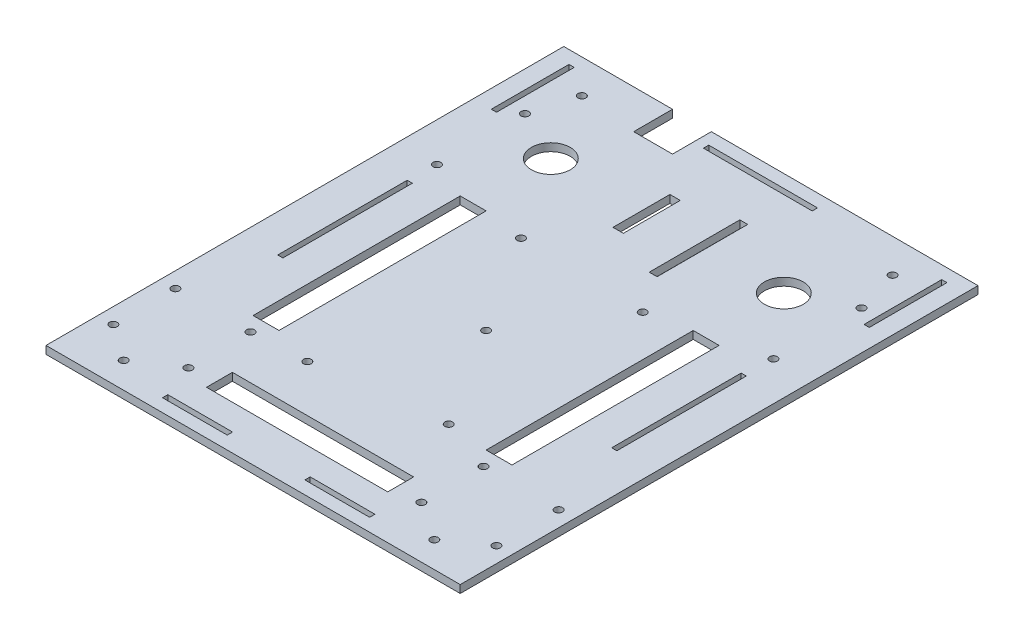
SolidWorks part; units mm, degrees
ref_plane "Front Plane" through (0, 0, 0) normal (0, 0, 1) x (1, 0, 0)
ref_plane "Top Plane" through (0, 0, 0) normal (0, 1, 0) x (1, 0, 0)
ref_plane "Right Plane" through (0, 0, 0) normal (1, 0, 0) x (0, 0, -1)
sketch "Sketch1" plane through (0, 0, 0) normal (0, 1, 0) x (1, 0, 0)
  line L1 (80, -100) -> (-80, -100)
  line L2 (80, -100) -> (80, 100)
  line L3 (80, 100) -> (-80, 100)
  line L4 (-80, -100) -> (-80, 100)
  line L5 (80, -100) -> (-80, 100) construction
  line L6 (80, 100) -> (-80, -100) construction
  point P0 (0, 0)
  dimension "D1" = 200
  dimension "D2" = 160
extrude "Boss-Extrude1" add sketch "Sketch1" along normal blind 3
sketch "Sketch2" plane through (0, 3, 0) normal (0, 1, 0) x (1, 0, 0)
  line L0 (-80, -100) -> (80, -100) construction
  line L1 (-80, 100) -> (-80, -100) construction
  line L2 (-3.268, 0) -> (0, 0) construction
  line L3 (0, 0) -> (0, -105.3922) construction
  line L4 (40, -92.95) -> (40, -95)
  line L5 (-40, -92.95) -> (-15, -92.95)
  line L6 (-40, -92.95) -> (-40, -95)
  line L7 (-40, -95) -> (-15, -95)
  line L8 (-15, -92.95) -> (-15, -95)
  line L9 (-40, -92.95) -> (-15, -95) construction
  line L10 (-40, -95) -> (-15, -92.95) construction
  line L11 (15, -92.95) -> (15, -95)
  line L12 (40, -95) -> (15, -95)
  line L13 (40, -92.95) -> (15, -92.95)
  line L14 (80, 100) -> (-80, 100) construction
  line L15 (65.5, -25) -> (63.5, -25)
  line L16 (-65.5, -25) -> (-63.5, -25)
  line L17 (-65.5, -25) -> (-65.5, 25)
  line L18 (-65.5, 25) -> (-63.5, 25)
  line L19 (-63.5, -25) -> (-63.5, 25)
  line L20 (-65.5, -25) -> (-63.5, 25) construction
  line L21 (-65.5, 25) -> (-63.5, -25) construction
  line L22 (63.5, -25) -> (63.5, 25)
  line L23 (65.5, -25) -> (65.5, 25)
  line L24 (65.5, 25) -> (63.5, 25)
  line L25 (73, 65) -> (70.98, 65)
  line L26 (-23, 85) -> (-38, 85)
  line L27 (-23, 85) -> (-23, 100)
  line L28 (-23, 100) -> (-38, 100)
  line L29 (-38, 85) -> (-38, 100)
  line L30 (-23, 85) -> (-38, 100) construction
  line L31 (-23, 100) -> (-38, 85) construction
  line L32 (23, 92.95) -> (-19, 92.95)
  line L33 (23, 92.95) -> (23, 95)
  line L34 (23, 95) -> (-19, 95)
  line L35 (-19, 92.95) -> (-19, 95)
  line L36 (23, 92.95) -> (-19, 95) construction
  line L37 (23, 95) -> (-19, 92.95) construction
  line L38 (-73, 95) -> (-70.98, 95)
  line L39 (-73, 95) -> (-73, 65)
  line L40 (-73, 65) -> (-70.98, 65)
  line L41 (-70.98, 95) -> (-70.98, 65)
  line L42 (-73, 95) -> (-70.98, 65) construction
  line L43 (-73, 65) -> (-70.98, 95) construction
  line L44 (70.98, 95) -> (70.98, 65)
  line L45 (73, 95) -> (73, 65)
  line L46 (73, 95) -> (70.98, 95)
  line L48 (-10, 49) -> (-6, 49)
  line L49 (-10, 49) -> (-10, 71)
  line L50 (-10, 71) -> (-6, 71)
  line L51 (-6, 49) -> (-6, 71)
  line L52 (-10, 49) -> (-6, 71) construction
  line L53 (-10, 71) -> (-6, 49) construction
  line L54 (15.05, 41) -> (12, 41)
  line L55 (15.05, 41) -> (15.05, 76)
  line L56 (15.05, 76) -> (12, 76)
  line L57 (12, 41) -> (12, 76)
  line L58 (15.05, 41) -> (12, 76) construction
  line L59 (15.05, 76) -> (12, 41) construction
  circle A0 centre (-60, -90) radius 1.5
  circle A1 centre (60, -90) radius 1.5
  circle A2 centre (0, -10) radius 1.5
  circle A3 centre (-65, 70) radius 1.5
  circle A4 centre (65, 70) radius 1.5
  point P14 (-27.5, -93.975)
  point P29 (-64.5, 0)
  point P38 (-30.5, 92.5)
  point P43 (2, 93.975)
  point P48 (-71.99, 80)
  point P57 (-8, 60)
  point P62 (13.525, 58.5)
  dimension "D1" = 3
  dimension "D4" = 3
  dimension "D10" = 3
  dimension "D11" = 30
  dimension "D12" = 15
  dimension "D2" = 10
  dimension "D3" = 20
  dimension "D5" = 90
  dimension "D6" = 40
  dimension "D7" = 2.05
  dimension "D8" = 5
  dimension "D9" = 25
  dimension "D13" = 50
  dimension "D14" = 75
  dimension "D15" = 2
  dimension "D16" = 14.5
  dimension "D17" = 23
  dimension "D18" = 15
  dimension "D19" = 15
  dimension "D20" = 5
  dimension "D21" = 2.05
  dimension "D22" = 42
  dimension "D23" = 2
  dimension "D24" = 30
  dimension "D25" = 5
  dimension "D26" = 2.02
  dimension "D27" = 7
  dimension "D28" = 29
  dimension "D29" = 22
  dimension "D30" = 4
  dimension "D31" = 10
  dimension "D32" = 3.05
  dimension "D33" = 24
  dimension "D34" = 35
  dimension "D35" = 12
extrude "Cut-Extrude1" cut sketch "Sketch2" against normal blind 3
sketch "Sketch3" plane through (0, 3, 0) normal (0, 1, 0) x (1, 0, 0)
  line L0 (-80, -100) -> (80, -100) construction
  line L1 (26.67, -60) -> (-26.67, -60)
  line L2 (26.67, -60) -> (26.67, 50)
  line L3 (26.67, 50) -> (-26.67, 50)
  line L4 (-26.67, -60) -> (-26.67, 50)
  line L5 (26.67, -60) -> (-26.67, 50) construction
  line L6 (26.67, 50) -> (-26.67, -60) construction
  line L7 (0, 0) -> (0, -100) construction
  circle A0 centre (-24.13, 27.6) radius 1.5
  circle A1 centre (24.13, 26.36) radius 1.5
  circle A2 centre (-24.13, -54.92) radius 1.5
  circle A3 centre (24.13, -48.57) radius 1.5
  point P0 (0, -5)
  dimension "D5" = 3
  dimension "D7" = 2.54
  dimension "D8" = 3
  dimension "D9" = 23.64
  dimension "D10" = 50.8
  dimension "D11" = 3
  dimension "D12" = 104.92
  dimension "D13" = 2.54
  dimension "D14" = 3
  dimension "D15" = 98.57
  dimension "D1" = 40
  dimension "D2" = 110
  dimension "D3" = 53.34
  dimension "D4" = 0
  dimension "D6" = 22.4
  dimension "D16" = 50.8
extrude "Cut-Extrude2" cut sketch "Sketch3" against normal through all contours A0 | A1 | A2 | A3
sketch "Sketch4" plane through (0, 3, 0) normal (0, 1, 0) x (1, 0, 0)
  line L0 (-80, -100) -> (80, -100) construction
  line L1 (-50, -50) -> (-40, -50)
  line L2 (-50, -50) -> (-50, 30)
  line L3 (-50, 30) -> (-40, 30)
  line L4 (-40, -50) -> (-40, 30)
  line L5 (-50, -50) -> (-40, 30) construction
  line L6 (-50, 30) -> (-40, -50) construction
  line L7 (-80, 100) -> (-80, -100) construction
  line L8 (0, 0) -> (0, -100) construction
  line L9 (50, -50) -> (40, -50)
  line L10 (40, -50) -> (40, 30)
  line L11 (50, -50) -> (50, 30)
  line L12 (50, 30) -> (40, 30)
  line L13 (-38, 100) -> (-80, 100) construction
  line L14 (35, -83) -> (-35, -83)
  line L15 (35, -83) -> (35, -73)
  line L16 (35, -73) -> (-35, -73)
  line L17 (-35, -83) -> (-35, -73)
  line L18 (35, -83) -> (-35, -73) construction
  line L19 (35, -73) -> (-35, -83) construction
  line L20 (-38, 100) -> (-80, 100) construction
  circle A0 centre (-45, 60) radius 7.5
  circle A1 centre (45, 60) radius 7.5
  circle A2 centre (-60, 87) radius 1.5
  circle A3 centre (60, 87) radius 1.5
  circle A4 centre (-65, 36) radius 1.5
  circle A5 centre (65, 36) radius 1.5
  point P0 (-45, -10)
  point P16 (0, -78)
  point P23 (-59, 100)
  dimension "D8" = 15
  dimension "D9" = 40
  dimension "D10" = 35
  dimension "D11" = 3
  dimension "D12" = 11.5
  dimension "D13" = 20
  dimension "D14" = 3
  dimension "D15" = 62.5
  dimension "D16" = 15
  dimension "D1" = 10
  dimension "D2" = 50
  dimension "D3" = 30
  dimension "D4" = 80
  dimension "D5" = 10
  dimension "D6" = 17
  dimension "D7" = 70
extrude "Cut-Extrude3" cut sketch "Sketch4" against normal blind 3
sketch "Sketch5" plane through (0, 3, 0) normal (0, 1, 0) x (1, 0, 0)
  line L0 (-80, -100) -> (80, -100) construction
  line L2 (-80, 100) -> (-80, -100) construction
  line L3 (-59.5, -56) -> (-59.5, -80) construction
  line L4 (0, 0) -> (0, -100) construction
  circle A0 centre (-74, -80) radius 1.5
  circle A1 centre (-74, -56) radius 1.5
  circle A2 centre (-45, -80) radius 1.5
  circle A3 centre (-45, -56) radius 1.5
  circle A4 centre (45, -80) radius 1.5
  circle A5 centre (45, -56) radius 1.5
  circle A6 centre (74, -80) radius 1.5
  circle A7 centre (74, -56) radius 1.5
  dimension "D1" = 3
  dimension "D2" = 20
  dimension "D3" = 6
  dimension "D4" = 3
  dimension "D6" = 6
  dimension "D7" = 14.5
  dimension "D5" = 24
  dimension "D8" = 14.5
  dimension "D9" = 20
extrude "Cut-Extrude4" cut sketch "Sketch5" against normal blind 10
